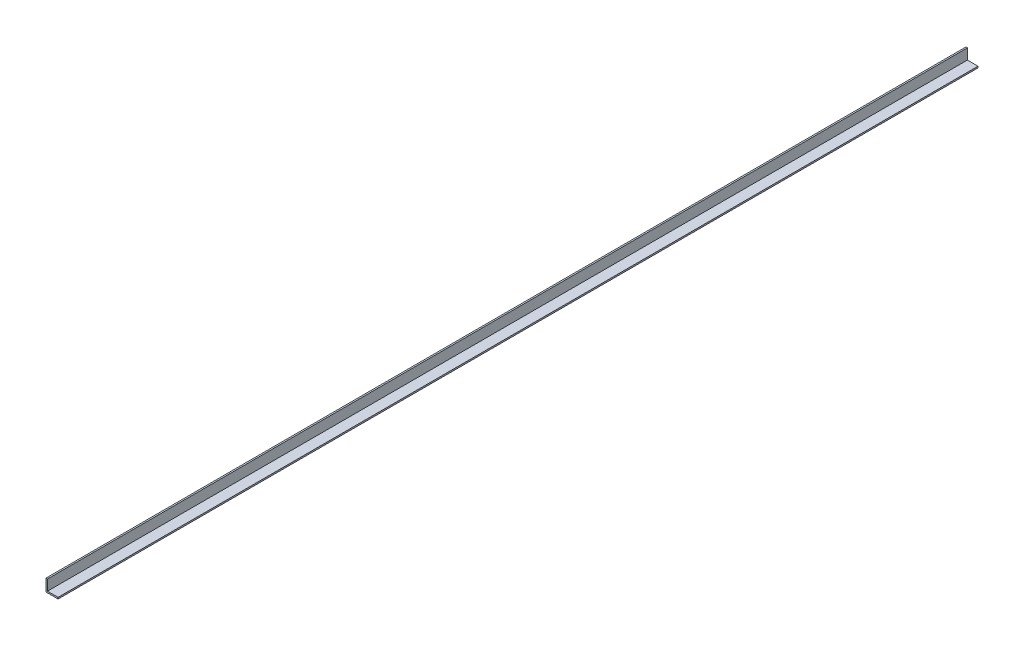
SolidWorks part; units mm, degrees
material "Plain Carbon Steel"
ref_plane "Front Plane" through (0, 0, 0) normal (0, 0, 1) x (1, 0, 0)
ref_plane "Top Plane" through (0, 0, 0) normal (0, 1, 0) x (1, 0, 0)
ref_plane "Right Plane" through (0, 0, 0) normal (1, 0, 0) x (0, 0, -1)
sketch "Sketch1" plane through (0, 0, 0) normal (0, 0, 1) x (1, 0, 0)
  line L0 (0, 0) -> (0, 25.4)
  line L1 (0, 25.4) -> (3.175, 25.4)
  line L2 (3.175, 25.4) -> (3.175, 3.175)
  line L3 (3.175, 3.175) -> (25.4, 3.175)
  line L4 (25.4, 3.175) -> (25.4, 0)
  line L5 (25.4, 0) -> (0, 0)
  dimension "D1" = 25.4
  dimension "D2" = 3.175
  dimension "D3" = 25.4
  dimension "D4" = 3.175
extrude "Boss-Extrude1" add sketch "Sketch1" along normal blind 1930.4
